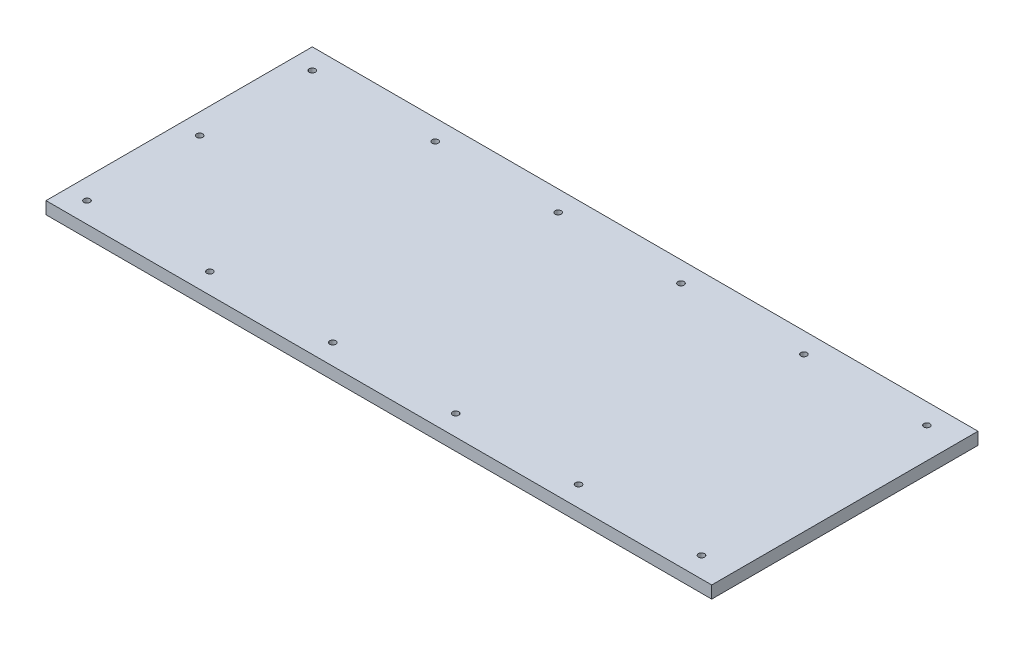
SolidWorks part; units mm, degrees
ref_plane "前视基准面" through (0, 0, 0) normal (0, 0, 1) x (1, 0, 0)
ref_plane "上视基准面" through (0, 0, 0) normal (0, 1, 0) x (1, 0, 0)
ref_plane "右视基准面" through (0, 0, 0) normal (1, 0, 0) x (0, 0, -1)
sketch "草图1" plane through (0, 0, 0) normal (0, 1, 0) x (1, 0, 0)
  line L0 (-162.5, -55) -> (162.5, -55) construction
  line L1 (-162.5, 65) -> (162.5, 65)
  line L2 (-162.5, 65) -> (-162.5, -65)
  line L3 (-162.5, -65) -> (162.5, -65)
  line L4 (162.5, 65) -> (162.5, -65)
  line L5 (-162.5, 55) -> (162.5, 55) construction
  line L6 (-152.5, 65) -> (-152.5, -65) construction
  circle A0 centre (-152.5, 55) radius 1.5
  circle A1 centre (-152.5, -55) radius 1.5
  circle A2 centre (-92.5, 55) radius 1.5
  circle A3 centre (-32.5, 55) radius 1.5
  circle A4 centre (27.5, 55) radius 1.5
  circle A5 centre (87.5, 55) radius 1.5
  circle A6 centre (147.5, 55) radius 1.5
  circle A7 centre (-92.5, -55) radius 1.5
  circle A8 centre (-32.5, -55) radius 1.5
  circle A9 centre (27.5, -55) radius 1.5
  circle A10 centre (87.5, -55) radius 1.5
  circle A11 centre (147.5, -55) radius 1.5
  circle A12 centre (-152.5, 0) radius 1.5
  dimension "D8" = 3
  dimension "D9" = 3
  dimension "D12" = 3
  dimension "D1" = 325
  dimension "D2" = 130
  dimension "D3" = 65
  dimension "D4" = 162.5
  dimension "D5" = 10
  dimension "D6" = 10
  dimension "D7" = 10
  dimension "D10" = 6
  dimension "D11" = 6
extrude "凸台-拉伸1" add sketch "草图1" along normal blind 6
